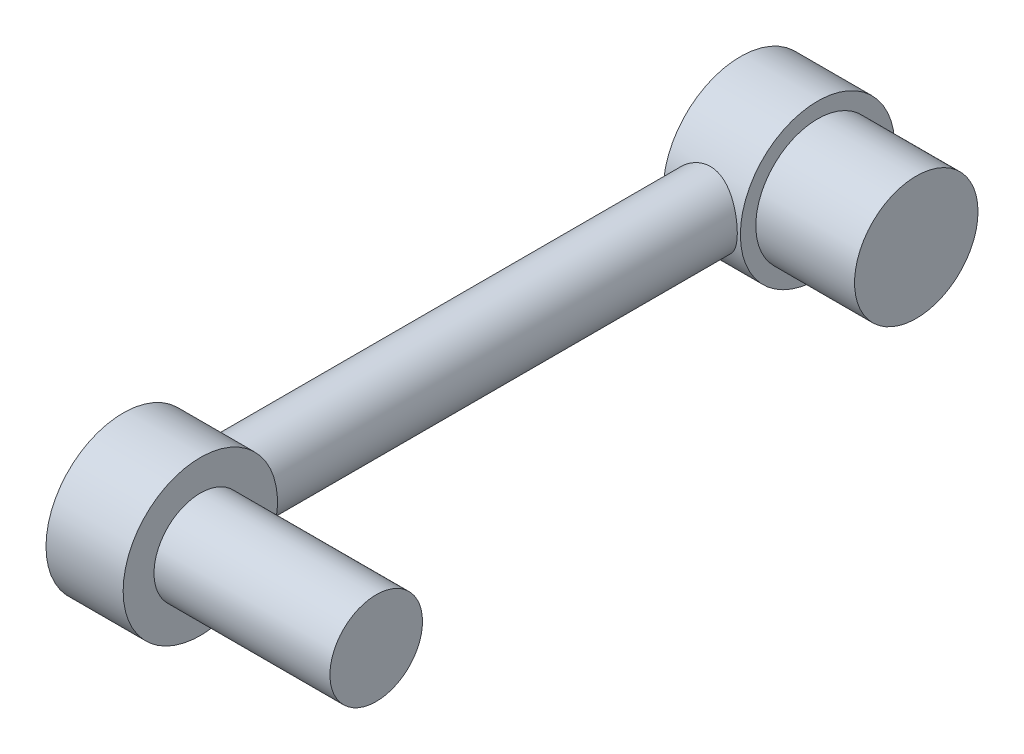
SolidWorks part; units mm, degrees
ref_plane "Front Plane" through (0, 0, 0) normal (0, 0, 1) x (1, 0, 0)
ref_plane "Top Plane" through (0, 0, 0) normal (0, 1, 0) x (1, 0, 0)
ref_plane "Right Plane" through (0, 0, 0) normal (1, 0, 0) x (0, 0, -1)
sketch "Sketch1" plane through (0, 0, 0) normal (0, 0, 1) x (1, 0, 0)
  circle A0 centre (0, 0) radius 29.21
  dimension "D1" = 58.42
extrude "Boss-Extrude1" add sketch "Sketch1" along normal blind 406.4
sketch "Sketch2" plane through (0, 0, 0) normal (0, 1, 0) x (1, 0, 0)
  line L1 (-31.75, 50.8) -> (31.75, 50.8)
  line L2 (-31.75, 50.8) -> (-31.75, -12.7)
  line L3 (-31.75, -12.7) -> (31.75, -12.7)
  line L4 (31.75, 50.8) -> (31.75, -12.7)
  dimension "D1" = 31.75
  dimension "D2" = 63.5
  dimension "D3" = 63.5
  dimension "D4" = 12.7
revolve "Revolve1" add sketch "Sketch2" angle 360 about L1
sketch "Sketch3" plane through (31.75, 0, 0) normal (1, 0, 0) x (0, 0, -1)
  circle A0 centre (50.8, 0) radius 50.8
  dimension "D1" = 101.6
extrude "Boss-Extrude2" add sketch "Sketch3" along normal blind 81.28
sketch "Sketch5" plane through (-31.75, 0, 0) normal (-1, 0, 0) x (0, 0, 1)
  circle A0 centre (-50.8, 0) radius 50.8 construction
  circle A1 centre (-50.8, 0) radius 50.8
sketch "Sketch10" plane through (0, 0, 0) normal (0, 1, 0) x (1, 0, 0)
  line L0 (-29.21, -406.4) -> (29.21, -406.4) construction
  line L1 (-31.75, -393.7) -> (31.75, -393.7)
  line L2 (-31.75, -393.7) -> (-31.75, -457.2)
  line L3 (-31.75, -457.2) -> (31.75, -457.2)
  line L4 (31.75, -393.7) -> (31.75, -457.2)
  dimension "D1" = 31.75
  dimension "D2" = 63.5
  dimension "D3" = 12.7
  dimension "D4" = 63.5
revolve "Revolve2" add sketch "Sketch10" angle 360 about L3
extrude "Cut-Extrude1" cut sketch "Sketch5" against normal blind 40.64 contours A1
sketch "Sketch11" plane through (31.75, 0, 0) normal (1, 0, 0) x (0, 0, -1)
  circle A0 centre (-457.2, 0) radius 38.1
  dimension "D1" = 76.2
extrude "Boss-Extrude4" add sketch "Sketch11" along normal blind 144.78
sketch "Sketch16" plane through (-31.75, 0, 0) normal (-1, 0, 0) x (0, 0, 1)
  circle A0 centre (457.2, 0) radius 38.1 construction
  circle A1 centre (457.2, 0) radius 38.1
extrude "Cut-Extrude2" cut sketch "Sketch16" against normal blind 12.7
scale "Scale1" scale about centroid uniform scaling yes scale factor 0.03937
